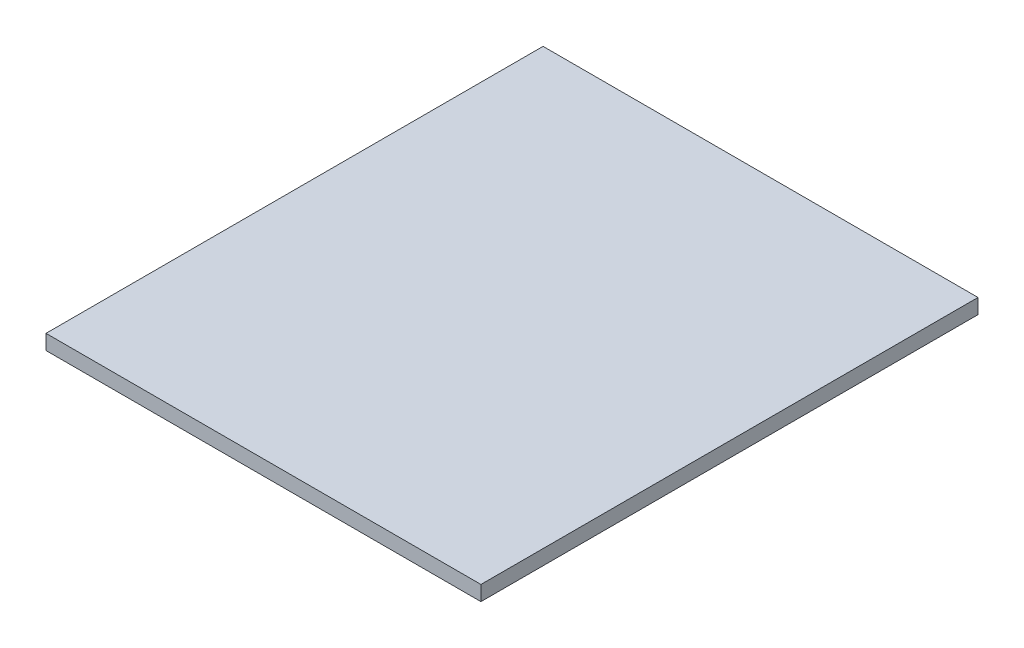
SolidWorks part; units mm, degrees
material "Pine"
ref_plane "Front Plane" through (0, 0, 0) normal (0, 0, 1) x (1, 0, 0)
ref_plane "Top Plane" through (0, 0, 0) normal (0, 1, 0) x (1, 0, 0)
ref_plane "Right Plane" through (0, 0, 0) normal (1, 0, 0) x (0, 0, -1)
sketch "Sketch1" plane through (0, 0, 0) normal (0, 1, 0) x (1, 0, 0)
  line L5 (0, 0) -> (175, 0)
  line L6 (0, 0) -> (0, -200)
  line L7 (0, -200) -> (175, -200)
  line L8 (175, 0) -> (175, -200)
  dimension "D1" = 175
  dimension "D2" = 200
extrude "Boss-Extrude1" add sketch "Sketch1" along normal blind 6
equation "\"BoardThickness\"= 6"
equation "\"D1@Boss-Extrude1\"=\"BoardThickness\""
